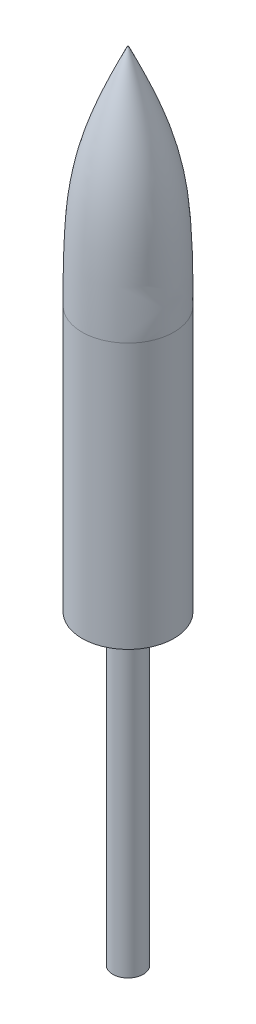
SolidWorks part; units mm, degrees
material "Hexcel AS4C (3000 Filaments)"
ref_plane "Front Plane" through (0, 0, 0) normal (0, 0, 1) x (1, 0, 0)
ref_plane "Top Plane" through (0, 0, 0) normal (0, 1, 0) x (1, 0, 0)
ref_plane "Right Plane" through (0, 0, 0) normal (1, 0, 0) x (0, 0, -1)
sketch "Sketch3" plane through (0, 0, 0) normal (0, 0, 1) x (1, 0, 0)
  line L0 (0, 44.736) -> (0, -44.3925) construction
  line L1 (0, 0) -> (3, 0)
  line L2 (3, 0) -> (3, 17.3271)
  line L3 (0, 0) -> (0, 32)
  spline S0 degree 2 poles (0, 32) (0.0206, 31.9999) (0.0375, 31.9869) knots 0 0 0 1 1 1
  spline S1 degree 3 poles (0.0375, 31.9869) (2.7943, 26.0505) (3, 24.0511) (3, 17.3271) knots 0 0 0 0 1 1 1 1
  dimension "D2" = 3
  dimension "D1" = 32
revolve "Revolve4" add sketch "Sketch3" angle 360 about L0
sketch "Sketch4" plane through (0, 0, 0) normal (0, -1, 0) x (1, 0, 0)
  circle A0 centre (0, 0) radius 1
extrude "Boss-Extrude1" add sketch "Sketch4" along normal blind 20
